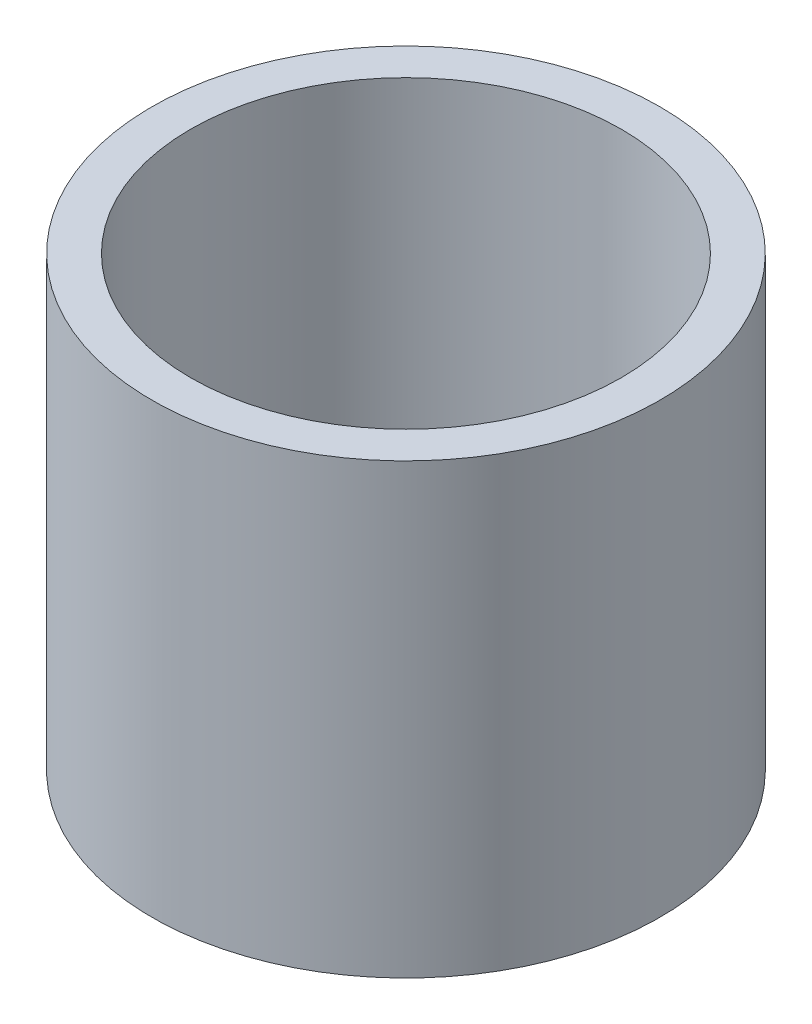
SolidWorks part; units mm, degrees
ref_plane "Спереди" through (0, 0, 0) normal (0, 0, 1) x (1, 0, 0)
ref_plane "Сверху" through (0, 0, 0) normal (0, 1, 0) x (1, 0, 0)
ref_plane "Справа" through (0, 0, 0) normal (1, 0, 0) x (0, 0, -1)
sketch "Эскиз1" plane through (0, 0, 0) normal (0, 0, 1) x (1, 0, 0)
  line L0 (0, 0) -> (0, 13983.1794) construction
  line L6 (-29.5, 52) -> (-25, 52)
  line L7 (-29.5, 52) -> (-29.5, 0)
  line L8 (-29.5, 0) -> (-25, 0)
  line L9 (-25, 52) -> (-25, 0)
  dimension "D1" = 50
  dimension "D2" = 52
  dimension "D3" = 59
revolve "Повернуть1" add sketch "Эскиз1" angle 360 about L0
